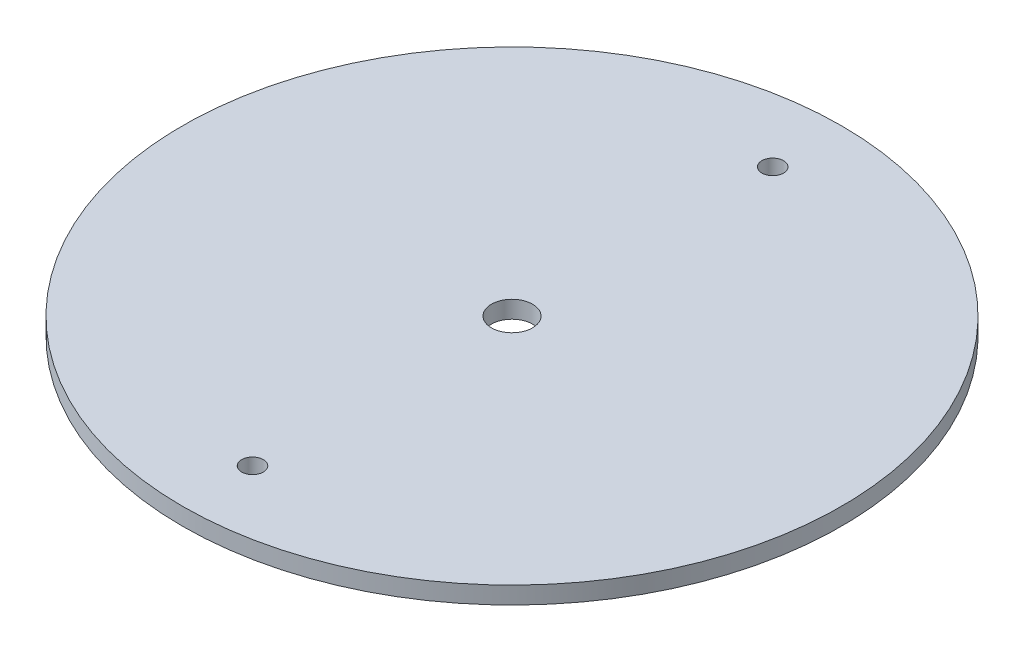
SolidWorks part; units mm, degrees
material "1060 Alloy"
ref_plane "Front Plane" through (0, 0, 0) normal (0, 0, 1) x (1, 0, 0)
ref_plane "Top Plane" through (0, 0, 0) normal (0, 1, 0) x (1, 0, 0)
ref_plane "Right Plane" through (0, 0, 0) normal (1, 0, 0) x (0, 0, -1)
sketch "Sketch1" plane through (0, 0, 0) normal (0, 1, 0) x (1, 0, 0)
  circle A0 centre (0, 0) radius 76.2
  circle A1 centre (0, 0) radius 4.75
  dimension "D1" = 152.4
  dimension "D2" = 9.5
extrude "Boss-Extrude1" add sketch "Sketch1" along normal blind 4
sketch "Sketch2" plane through (0, 4, 0) normal (0, 1, 0) x (1, 0, 0)
  circle A0 centre (0, -60) radius 2.5
  circle A1 centre (0.2778, 59.9994) radius 2.5
  point P2 (0, -60)
  point P8 (0, 0)
  dimension "D1" = 5
  dimension "D2" = 60
  dimension "D3" = 2
extrude "Cut-Extrude1" cut sketch "Sketch2" against normal up to next
